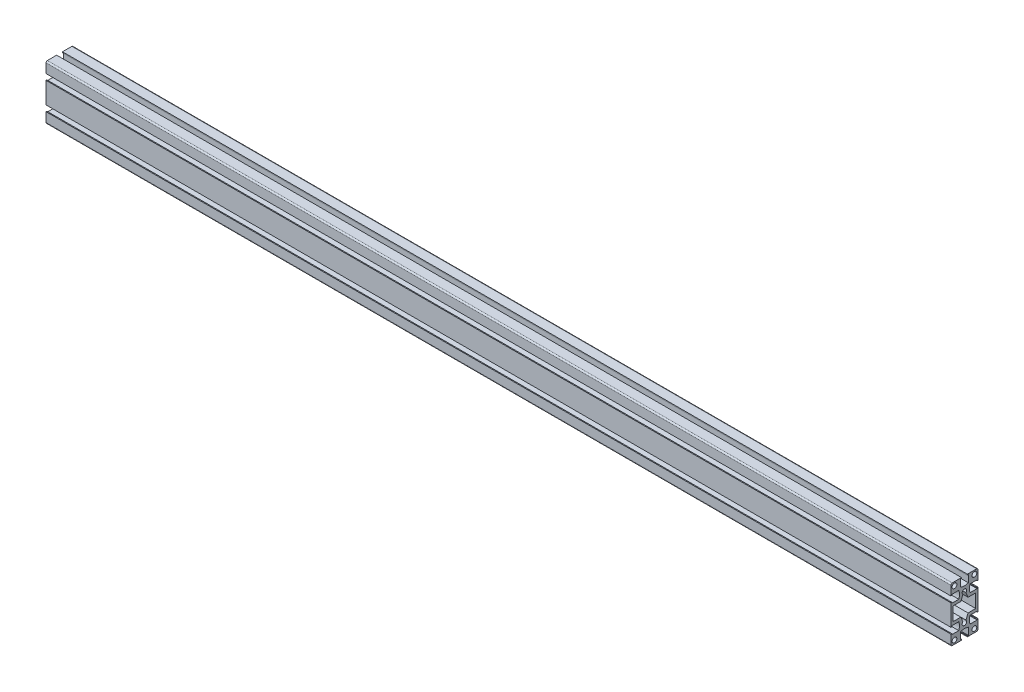
SolidWorks part; units mm, degrees
material "6063-T5"
ref_plane "前视基准面" through (0, 0, 0) normal (0, 0, 1) x (1, 0, 0)
ref_plane "上视基准面" through (0, 0, 0) normal (0, 1, 0) x (1, 0, 0)
ref_plane "右视基准面" through (0, 0, 0) normal (1, 0, 0) x (0, 0, -1)
other "Configuration Table"
sketch "草图1" plane through (0, 0, 0) normal (0, 1, 0) x (1, 0, 0)
  line L0 (0, 0) -> (1000, 0)
  dimension "D1" = 1000
other "工业铝型材 30 X 60G X R1.5(1)"
ref_plane "基准面1" through (0, 0, 0) normal (1, 0, 0) x (0, 0, -1)
sketch "Sketch12" plane through (0, 0, 0) normal (1, 0, 0) x (0, 0, -1)
  line L0 (-3.25, 30) -> (-3.25, 29)
  line L1 (-13.5, 30) -> (-3.25, 30)
  line L2 (-15, 28.5) -> (-15, 18.25)
  line L3 (-13.5, -30) -> (-3.25, -30)
  line L4 (15, 28.5) -> (15, 18.25)
  line L5 (-12.5, 7.5) -> (-4, 7.5)
  line L6 (-12.5, 7.5) -> (-12.5, -7.5)
  line L7 (-12.5, -7.5) -> (-4, -7.5)
  line L8 (0, 30) -> (0, 0) construction
  line L9 (0, 0) -> (15, 0) construction
  line L10 (12.5, 7.5) -> (12.5, -7.5)
  line L11 (-3.25, 29) -> (-4.25, 29)
  line L12 (-4.25, 29) -> (-4.25, 21.2778)
  line L13 (-11, 26) -> (-15, 30) construction
  line L14 (4.25, 29) -> (4.25, 21.2778)
  line L15 (3.25, 29) -> (4.25, 29)
  line L16 (3.25, 30) -> (3.25, 29)
  line L17 (3.25, 30) -> (13.5, 30)
  line L18 (-1.6656, 13.1357) -> (-4, 7.5)
  line L19 (1.6656, 13.1357) -> (4, 7.5)
  line L20 (4, 7.5) -> (12.5, 7.5)
  line L21 (1.6656, -13.1357) -> (4, -7.5)
  line L22 (-1.6656, -13.1357) -> (-4, -7.5)
  line L23 (4, -7.5) -> (12.5, -7.5)
  line L24 (15, 18.25) -> (14, 18.25)
  line L25 (14, 18.25) -> (14, 19.25)
  line L26 (14, 19.25) -> (6.2778, 19.25)
  line L27 (14, 10.75) -> (6.2778, 10.75)
  line L28 (14, 11.75) -> (14, 10.75)
  line L29 (15, 11.75) -> (14, 11.75)
  line L30 (3.25, 0) -> (3.25, 1) [skipped]
  line L31 (3.25, 1) -> (4.25, 1) [skipped]
  line L32 (4.25, 1) -> (4.25, 8.7222) [skipped]
  line L33 (-4.25, 1) -> (-4.25, 8.7222) [skipped]
  line L34 (-3.25, 1) -> (-4.25, 1) [skipped]
  line L35 (-3.25, 0) -> (-3.25, 1) [skipped]
  line L36 (-15, 11.75) -> (-14, 11.75)
  line L37 (-14, 11.75) -> (-14, 10.75)
  line L38 (-14, 10.75) -> (-6.2778, 10.75)
  line L39 (-14, 19.25) -> (-6.2778, 19.25)
  line L40 (-14, 18.25) -> (-14, 19.25)
  line L41 (-15, 18.25) -> (-14, 18.25)
  line L42 (-15, 11.75) -> (-15, -11.75)
  line L43 (15, 11.75) -> (15, -11.75)
  line L44 (-15, -18.25) -> (-14, -18.25)
  line L45 (-14, -18.25) -> (-14, -19.25)
  line L46 (-14, -19.25) -> (-6.2778, -19.25)
  line L47 (-14, -10.75) -> (-6.2778, -10.75)
  line L48 (-14, -11.75) -> (-14, -10.75)
  line L49 (-15, -11.75) -> (-14, -11.75)
  line L50 (15, -11.75) -> (14, -11.75)
  line L51 (14, -11.75) -> (14, -10.75)
  line L52 (14, -10.75) -> (6.2778, -10.75)
  line L53 (14, -19.25) -> (6.2778, -19.25)
  line L54 (14, -18.25) -> (14, -19.25)
  line L55 (15, -18.25) -> (14, -18.25)
  line L56 (3.25, -30) -> (3.25, -29)
  line L57 (3.25, -29) -> (4.25, -29)
  line L58 (4.25, -29) -> (4.25, -21.2778)
  line L59 (-4.25, -29) -> (-4.25, -21.2778)
  line L60 (-3.25, -29) -> (-4.25, -29)
  line L61 (-3.25, -30) -> (-3.25, -29)
  line L62 (3.25, -30) -> (13.5, -30)
  line L63 (-15, -18.25) -> (-15, -28.5)
  line L64 (15, -18.25) -> (15, -28.5)
  arc A0 (-4.25, 21.2778) -> (4.25, 21.2778) centre (0, 32.5) ccw
  circle A1 centre (-11, 26) radius 2.65
  circle A2 centre (11, 26) radius 2.65
  arc A3 (-15, 28.5) -> (-13.5, 30) centre (-13.5, 28.5) cw
  arc A4 (15, 28.5) -> (13.5, 30) centre (13.5, 28.5) ccw
  arc A5 (15, -28.5) -> (13.5, -30) centre (13.5, -28.5) cw
  arc A6 (-13.5, -30) -> (-15, -28.5) centre (-13.5, -28.5) cw
  arc A7 (1.6656, 13.1357) -> (-1.6656, 13.1357) centre (0, 15) ccw
  arc A8 (-1.6656, -13.1357) -> (1.6656, -13.1357) centre (0, -15) ccw
  arc A9 (6.2778, 19.25) -> (6.2778, 10.75) centre (17.5, 15) ccw
  arc A10 (4.25, 8.7222) -> (-4.25, 8.7222) centre (0, -2.5) ccw [skipped]
  arc A11 (-6.2778, 10.75) -> (-6.2778, 19.25) centre (-17.5, 15) ccw
  arc A12 (-6.2778, -10.75) -> (-6.2778, -19.25) centre (-17.5, -15) cw
  arc A13 (6.2778, -19.25) -> (6.2778, -10.75) centre (17.5, -15) cw
  circle A14 centre (11, -26) radius 2.65
  arc A15 (-4.25, -21.2778) -> (4.25, -21.2778) centre (0, -32.5) cw
  circle A16 centre (-11, -26) radius 2.65
  point P102 (15, -30)
  point P103 (-15, -30)
  point P104 (0, 0)
  dimension "D1" = 60
  dimension "D2" = 30
  dimension "D3" = 15
  dimension "D4" = 2.5
  dimension "D5" = 6.5
  dimension "D6" = 8.5
  dimension "D7" = 12
  dimension "D8" = 1
  dimension "D10" = 5.3
  dimension "D11" = 4
  dimension "D12" = 1.5
  dimension "D13" = 5
  dimension "D14" = 30
  dimension "D9" = 9.5
  dimension "D15" = 45
  dimension "D16" = 8
